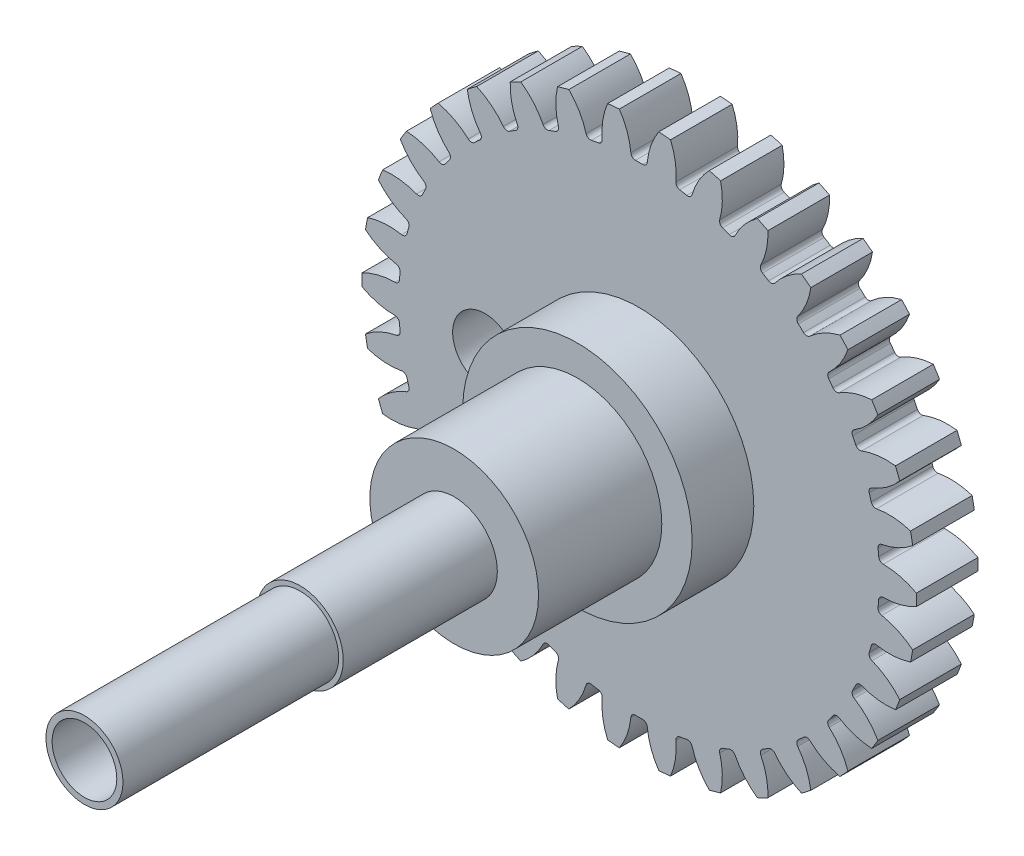
SolidWorks part; units mm, degrees
ref_plane "Front Plane" through (0, 0, 0) normal (0, 0, 1) x (1, 0, 0)
ref_plane "Top Plane" through (0, 0, 0) normal (0, 1, 0) x (1, 0, 0)
ref_plane "Right Plane" through (0, 0, 0) normal (1, 0, 0) x (0, 0, -1)
sketch "Sketch1" plane through (0, 0, 0) normal (0, 0, 1) x (1, 0, 0)
  circle A0 centre (0, 0) radius 8.5 construction
  circle A1 centre (0, 0) radius 9
  dimension "D1" = 17
  dimension "D2" = 18
extrude "Boss-Extrude1" add sketch "Sketch1" along normal mid plane 2
sketch "Sketch3" plane through (0, 0, 0) normal (0, 0, 1) x (1, 0, 0)
  line L0 (0, 9) -> (0, 0) construction
  line L1 (0, 0) -> (1.6537, 8.8468) construction
  line L2 (0, 0) -> (0.8304, 8.9616) construction
  line L3 (-0.2581, 7.7957) -> (0, 0) construction
  line L4 (-0.3926, 8.4909) -> (0.3926, 8.4909) construction
  line L5 (0.3926, 8.4909) -> (1.1743, 8.4185) construction
  line L6 (-0.5712, 8.9819) -> (0, 7.4124) construction
  circle A0 centre (0, 0) radius 8 construction
  arc A1 (0.2581, 7.7957) -> (-0.2581, 7.7957) centre (0, 0) ccw
  circle A2 centre (0, 0) radius 9 construction
  arc A3 (-0.6399, 8.9772) -> (-0.2581, 7.7957) centre (-2.5072, 7.7213) cw
  circle A5 centre (0, 0) radius 9 construction
  arc A6 (0.6399, 8.9772) -> (0.2581, 7.7957) centre (2.5072, 7.7213) ccw
  circle A7 centre (0, 0) radius 8.5 construction
  arc A9 (0.6399, 8.9772) -> (-0.6399, 8.9772) centre (0, 0) ccw
  dimension "D1" = 10.588
  dimension "D2" = 1
  dimension "D3" = 1.2
  dimension "D4" = 0.2
  dimension "D5" = 20
extrude "Cut-Extrude1" cut sketch "Sketch3" against normal through all both and the other way through all
fillet "Fillet1" radius 0.15 2 edges at (-0.2581, 7.7957, 0) (0.2581, 7.7957, 0)
pattern_circular "CirPattern1" count 34 over 360 about axis through (0, 0, 0) along (0, 0, 1) of "Fillet1", "Cut-Extrude1"
sketch "Sketch4" plane through (0, 0, 1) normal (0, 0, 1) x (1, 0, 0)
  circle A0 centre (0, 0) radius 1.05
  dimension "D1" = 2.1
extrude "Cut-Extrude2" cut sketch "Sketch4" against normal through all both
sketch "Sketch5" plane through (0, 0, 1) normal (0, 0, 1) x (1, 0, 0)
  line L0 (-5, 0) -> (0, 0) construction
  circle A0 centre (-5, 0) radius 1.05
  dimension "D1" = 2.1
  dimension "D2" = 5
extrude "Cut-Extrude3" cut sketch "Sketch5" against normal blind 10
sketch "Sketch6" plane through (0, 0, 1) normal (0, 0, 1) x (1, 0, 0)
  circle A0 centre (0, 0) radius 3.7234
extrude "Boss-Extrude2" add sketch "Sketch6" along normal blind 2
sketch "Sketch7" plane through (0, 0, 3) normal (0, 0, 1) x (1, 0, 0)
  circle A0 centre (0, 0) radius 2.7377
extrude "Boss-Extrude3" add sketch "Sketch7" along normal blind 4
sketch "Sketch8" plane through (0, 0, 7) normal (0, 0, 1) x (1, 0, 0)
  circle A0 centre (0, 0) radius 1.4
  dimension "D1" = 2.8
extrude "Boss-Extrude4" add sketch "Sketch8" along normal blind 5
sketch "Sketch9" plane through (0, 0, 12) normal (0, 0, 1) x (1, 0, 0)
  circle A0 centre (0, 0) radius 1.25
  dimension "D1" = 2.5
extrude "Boss-Extrude5" add sketch "Sketch9" along normal blind 7
sketch "Sketch10" plane through (0, 0, 1) normal (0, 0, -1) x (-1, 0, 0)
  circle A0 centre (0, 0) radius 1.05
extrude "Cut-Extrude4" cut sketch "Sketch10" against normal through all
equation "\"module\"= 0.5mm"
equation "\"number of teeth\"= 34"
equation "\"pressure angle\"= 20"
equation "\"D1@Sketch1\"= \"module\" * \"number of teeth\""
equation "\"D2@Sketch1\"=(\"number of teeth\" + 2) * \"module\" "
equation "\"D1@Sketch3\"=360 / \"number of teeth\""
equation "\"D3@Sketch3\"= \"module\"  * if( \"module\" => 1.25,2.25,2.4)"
equation "\"D5@Sketch3\"=\"pressure angle\""
equation "\"D1@Fillet1\"=0.3 * \"module\""
equation "\"D1@CirPattern1\"=\"number of teeth\""
equation "\"D1@Chamfer1\"=\"module\""
